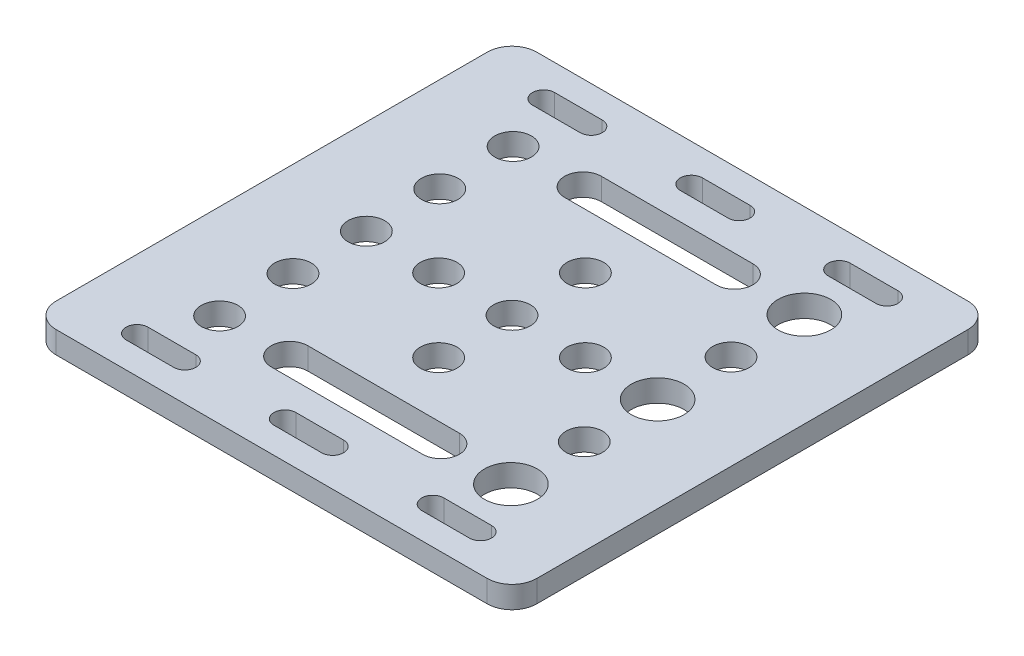
SolidWorks part; units mm, degrees
ref_plane "Front Plane" through (0, 0, 0) normal (0, 0, 1) x (1, 0, 0)
ref_plane "Top Plane" through (0, 0, 0) normal (0, 1, 0) x (1, 0, 0)
ref_plane "Right Plane" through (0, 0, 0) normal (1, 0, 0) x (0, 0, -1)
sketch "Sketch1" plane through (0, 0, 0) normal (0, 1, 0) x (1, 0, 0)
  line L0 (-10.32, 22.5) -> (10.32, 22.5)
  line L1 (10.32, 17.5) -> (-10.32, 17.5)
  line L2 (23.4, 26.2) -> (16.9, 26.2)
  line L3 (16.9, 29.2) -> (23.4, 29.2)
  line L4 (-23.4, 29.2) -> (-16.9, 29.2)
  line L5 (-16.9, 26.2) -> (-23.4, 26.2)
  line L6 (16.9, -26.2) -> (23.4, -26.2)
  line L7 (23.4, -29.2) -> (16.9, -29.2)
  line L8 (3.25, -29.2) -> (-3.25, -29.2)
  line L9 (-3.25, -26.2) -> (3.25, -26.2)
  line L10 (-23.4, -26.2) -> (-16.9, -26.2)
  line L11 (-16.9, -29.2) -> (-23.4, -29.2)
  line L12 (3.25, 26.2) -> (-3.25, 26.2)
  line L13 (-3.25, 29.2) -> (3.25, 29.2)
  line L14 (10.32, -22.5) -> (-10.32, -22.5)
  line L15 (-10.32, -17.5) -> (10.32, -17.5)
  line L16 (-32.75, 29.37) -> (-32.75, -29.37)
  line L17 (-29.37, -32.75) -> (29.37, -32.75)
  line L18 (32.75, -29.37) -> (32.75, 29.37)
  line L19 (29.37, 32.75) -> (-29.37, 32.75)
  circle A0 centre (19.85, -20) radius 3.6
  circle A1 centre (19.85, 0) radius 3.6
  circle A2 centre (19.85, 10) radius 2.5
  circle A3 centre (-19.85, 10) radius 2.5
  circle A4 centre (-19.85, -10) radius 2.5
  circle A5 centre (10, 0) radius 2.5
  circle A6 centre (-10, 0) radius 2.5
  circle A7 centre (0, 0) radius 2.5
  circle A8 centre (0, 10) radius 2.5
  circle A9 centre (0, -10) radius 2.5
  circle A10 centre (-19.85, 0) radius 2.5
  circle A11 centre (-19.85, -20) radius 2.5
  circle A12 centre (-19.85, 20) radius 2.5
  circle A13 centre (19.85, -10) radius 2.5
  circle A14 centre (19.85, 20) radius 3.6
  arc A15 (-10.32, 17.5) -> (-10.32, 22.5) centre (-10.32, 20) cw
  arc A16 (10.32, 22.5) -> (10.32, 17.5) centre (10.32, 20) cw
  arc A17 (23.4, 29.2) -> (23.4, 26.2) centre (23.4, 27.7) cw
  arc A18 (16.9, 26.2) -> (16.9, 29.2) centre (16.9, 27.7) cw
  arc A19 (-23.4, 26.2) -> (-23.4, 29.2) centre (-23.4, 27.7) cw
  arc A20 (-16.9, 29.2) -> (-16.9, 26.2) centre (-16.9, 27.7) cw
  arc A21 (16.9, -29.2) -> (16.9, -26.2) centre (16.9, -27.7) cw
  arc A22 (23.4, -26.2) -> (23.4, -29.2) centre (23.4, -27.7) cw
  arc A23 (3.25, -26.2) -> (3.25, -29.2) centre (3.25, -27.7) cw
  arc A24 (-3.25, -29.2) -> (-3.25, -26.2) centre (-3.25, -27.7) cw
  arc A25 (-23.4, -29.2) -> (-23.4, -26.2) centre (-23.4, -27.7) cw
  arc A26 (-16.9, -26.2) -> (-16.9, -29.2) centre (-16.9, -27.7) cw
  arc A27 (3.25, 29.2) -> (3.25, 26.2) centre (3.25, 27.7) cw
  arc A28 (-3.25, 26.2) -> (-3.25, 29.2) centre (-3.25, 27.7) cw
  arc A29 (10.32, -17.5) -> (10.32, -22.5) centre (10.32, -20) cw
  arc A30 (-10.32, -22.5) -> (-10.32, -17.5) centre (-10.32, -20) cw
  arc A31 (-29.37, 32.75) -> (-32.75, 29.37) centre (-29.37, 29.37) ccw
  arc A32 (-32.75, -29.37) -> (-29.37, -32.75) centre (-29.37, -29.37) ccw
  arc A33 (29.37, -32.75) -> (32.75, -29.37) centre (29.37, -29.37) ccw
  arc A34 (32.75, 29.37) -> (29.37, 32.75) centre (29.37, 29.37) ccw
extrude "Boss-Extrude1" add sketch "Sketch1" along normal blind 3
